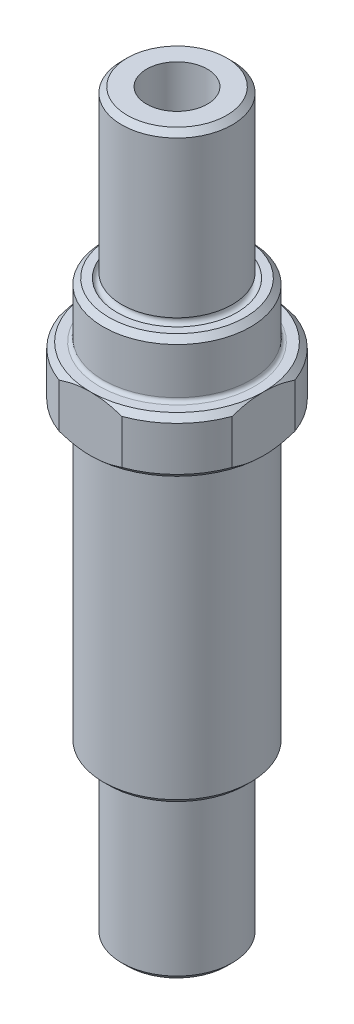
SolidWorks part; units mm, degrees
material "Chrome Stainless Steel"
ref_plane "Front Plane" through (0, 0, 0) normal (0, 0, 1) x (1, 0, 0)
ref_plane "Top Plane" through (0, 0, 0) normal (0, 1, 0) x (1, 0, 0)
ref_plane "Right Plane" through (0, 0, 0) normal (1, 0, 0) x (0, 0, -1)
sketch "Sketch1" plane through (0, 0, 0) normal (0, 0, 1) x (1, 0, 0)
  line L0 (-6, 5) -> (32.5648, 5) construction
  line L1 (-6, 9.7) -> (-6, 0.3) construction
  line L2 (27.4642, 25) -> (27.4642, -15)
  line L3 (27.4642, -15) -> (24.4642, -15)
  line L4 (24.4642, -15) -> (24.4642, -6)
  line L5 (24.4642, -6) -> (23.4642, -6)
  line L6 (23.4642, -6) -> (23.4642, 10)
  line L7 (23.4642, 10) -> (22.4642, 10)
  line L8 (22.4642, 10) -> (22.4642, 13)
  line L9 (22.4642, 13) -> (23.4642, 13)
  line L10 (23.4642, 13) -> (23.4642, 16)
  line L11 (23.4642, 16) -> (24.4642, 16)
  line L12 (24.4642, 16) -> (24.4642, 25)
  line L13 (24.4642, 25) -> (27.4642, 25)
  line L14 (18.7, 10) -> (-18.7, 10) construction
  dimension "D1" = 3
  dimension "D2" = 4
  dimension "D3" = 9
  dimension "D4" = 5
  dimension "D5" = 3
  dimension "D6" = 3
revolve "Revolve1" add sketch "Sketch1" angle 360 about L2
cosmetic thread "Cosmetic Thread1" parameters "D1"=10, "D2"=6.619
sketch "Sketch2" plane through (0, 0, 0) normal (0, 0, 1) x (1, 0, 0)
  line L0 (27.4642, 25) -> (27.4642, -15) construction
  line L1 (30.4642, 25) -> (24.4642, 25) construction
  line L2 (24.4642, -15) -> (30.4642, -15) construction
  circle A0 centre (24.4642, -6) radius 0.25
  circle A1 centre (23.4642, 10) radius 0.25
  circle A2 centre (24.4642, 16) radius 0.25
  dimension "D1" = 0.5
revolve "Cut-Revolve1" cut sketch "Sketch2" angle 360 about L0
chamfer "Chamfer1" distance 0.3 angle 45 6 edges at (27.4642, 13, 5) (27.4642, 10, 5) (27.4642, -6, 4) (27.4642, 16, 4) (27.4642, 25, 3) (27.4642, -15, 3)
fillet "Fillet1" radius 0.2 1 edges at (27.4642, 13, 4)
hole_wizard "M4x0.7 Tapped Hole1" positions "Sketch3" profile "Sketch5" tap size "M4x0.7" standard "ANSI Metric"
sketch "Sketch3" plane through (0, 25, 0) normal (0, 1, 0) x (1, 0, 0)
  point P0 (27.4642, 0)
sketch "Sketch5" plane through (27.4642, 25, 0) normal (1, 0, 0) x (0, 0, 1)
  line L0 (0, 0) -> (0, 10.9914)
  line L1 (0, 10.9914) -> (1.65, 10)
  line L2 (1.65, 10) -> (1.65, 0)
  line L5 (1.65, 0) -> (0, 0)
  line L10 (0, 10.9914) -> (-1.65, 10) construction
  line L11 (0, -6.35) -> (0, 107.95) construction
  dimension "Tap Drill Dia." = 3.3
  dimension "Tap Drill Depth" = 10
  dimension "Drill Angle" = 118
cosmetic thread "Hole Thread1" parameters "D1"=10, "D2"=4
hole_wizard "M4x0.7 Tapped Hole2" positions "Sketch6" profile "Sketch7" tap size "M4x0.7" standard "ANSI Metric"
sketch "Sketch6" plane through (0, -15, 0) normal (0, -1, 0) x (-1, 0, 0)
  point P0 (-27.4642, 0)
sketch "Sketch7" plane through (27.4642, -15, 0) normal (1, 0, 0) x (0, 0, -1)
  line L0 (0, 0) -> (0, 10.9914)
  line L1 (0, 10.9914) -> (1.65, 10)
  line L2 (1.65, 10) -> (1.65, 0)
  line L5 (1.65, 0) -> (0, 0)
  line L10 (0, 10.9914) -> (-1.65, 10) construction
  line L11 (0, -6.35) -> (0, 107.95) construction
  dimension "Tap Drill Dia." = 3.3
  dimension "Tap Drill Depth" = 10
  dimension "Drill Angle" = 118
cosmetic thread "Hole Thread2" parameters "D1"=10, "D2"=4
sketch "Sketch8" plane through (0, 0, 0) normal (0, 0, 1) x (1, 0, 0)
  line L0 (27.4642, 25) -> (27.4642, -15) construction
  line L1 (30.1642, 25) -> (24.7642, 25) construction
  line L2 (24.7642, -15) -> (30.1642, -15) construction
  line L3 (22.7642, 13) -> (22.7642, 10)
  line L5 (32.1642, 13) -> (32.1642, 10)
  line L6 (32.4642, 12.7) -> (32.1642, 13) construction
  line L7 (32.4642, 10.3) -> (32.4642, 12.7) construction
  line L8 (32.1642, 10) -> (32.4642, 10.3) construction
  line L9 (22.4642, 10.3) -> (22.7642, 10) construction
  line L10 (22.4642, 12.7) -> (22.4642, 10.3) construction
  line L11 (22.7642, 13) -> (22.4642, 12.7) construction
  line L12 (32.4642, 12.7) -> (32.1642, 13)
  line L13 (32.4642, 10.3) -> (32.4642, 12.7)
  line L14 (32.1642, 10) -> (32.4642, 10.3)
  line L15 (22.4642, 10.3) -> (22.7642, 10)
  line L16 (22.4642, 12.7) -> (22.4642, 10.3)
  line L17 (22.7642, 13) -> (22.4642, 12.7)
extrude "Cut-Extrude1" cut sketch "Sketch8" against normal through all both and the other way through all
pattern_circular "CirPattern1" count 4 over 360 about axis through (27.4642, 12.7, 0) along (0, 1, 0) of "Cut-Extrude1"
